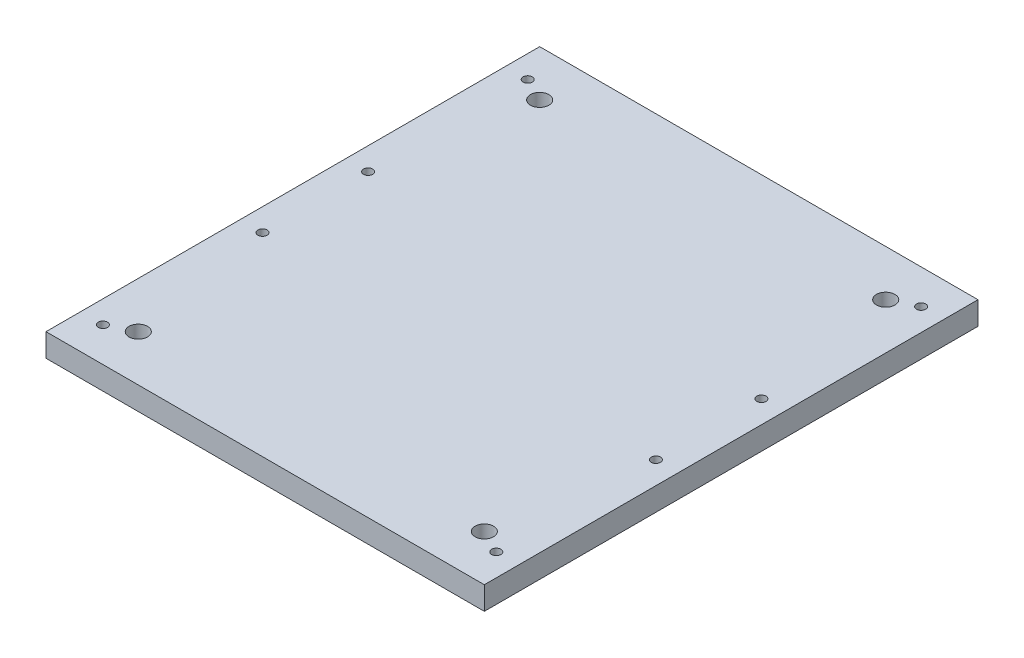
SolidWorks part; units mm, degrees
ref_plane "Front Plane" through (0, 0, 0) normal (0, 0, 1) x (1, 0, 0)
ref_plane "Top Plane" through (0, 0, 0) normal (0, 1, 0) x (1, 0, 0)
ref_plane "Right Plane" through (0, 0, 0) normal (1, 0, 0) x (0, 0, -1)
sketch "Sketch2" plane through (0, 0, 0) normal (0, 1, 0) x (1, 0, 0)
  line L0 (37.5, -43.5) -> (47.5, -43.5)
  line L1 (-47.5, -53.5) -> (47.5, -53.5)
  line L2 (-47.5, -53.5) -> (-47.5, 53.5)
  line L3 (-47.5, 53.5) -> (47.5, 53.5)
  line L4 (47.5, -53.5) -> (47.5, 53.5)
  line L5 (-47.5, -53.5) -> (47.5, 53.5) construction
  line L6 (-47.5, 53.5) -> (47.5, -53.5) construction
  line L7 (37.5, -43.5) -> (37.5, -53.5)
  line L8 (-55, 0) -> (55, 0) construction
  line L9 (0, -55) -> (0, 55) construction
  line L15 (-60, 66) -> (60, 66)
  line L16 (-60, 66) -> (-60, -66)
  line L17 (-60, -66) -> (60, -66)
  line L18 (60, 66) -> (60, -66)
  line L19 (-60, 66) -> (60, -66) construction
  line L20 (-60, -66) -> (60, 66) construction
  circle A1 centre (37.5, -43.5) radius 2
  circle A2 centre (37.5, 43.5) radius 2
  circle A3 centre (-37.5, -43.5) radius 2
  circle A4 centre (-37.5, 43.5) radius 2
  point P0 (0, 0)
  point P20 (0, 0)
  point P21 (0, 0)
  dimension "D3" = 10
  dimension "D5" = 4
  dimension "D1" = 95
  dimension "D2" = 107
  dimension "D4" = 10
  dimension "D6" = 120
  dimension "D7" = 132
extrude "Boss-Extrude1" add sketch "Sketch2" along normal blind 5 contours A1 L0 L4 L3 L2 L1 L7 A4 A2 A3 | A1 L7 L1 L4 L0
sketch "Sketch3" plane through (0, 5, 0) normal (0, 1, 0) x (1, 0, 0)
  line L5 (-47.515, 40.2371) -> (-32.4121, 40.2371) construction
  line L6 (-47.5, -53.5) -> (-47.5, 53.5) construction
  line L10 (-47.5, 17.2402) -> (-47.5, 40.2371)
  line L11 (-47.6, 40.3371) -> (-32.2822, 40.3371)
  line L12 (-32.2822, 40.3371) -> (-30.49, 37.2328)
  line L13 (-30.49, 17.1402) -> (-30.49, 37.2328)
  line L14 (-47.6, 17.1402) -> (-30.49, 17.1402)
  line L15 (-47.6, 17.1402) -> (-47.6, 40.3371)
  line L16 (-47.5, 40.2371) -> (-32.34, 40.2371) construction
  line L17 (-47.5, 17.2402) -> (-30.59, 17.2402) construction
  line L18 (-30.59, 17.2402) -> (-30.59, 37.206) construction
  line L19 (-32.34, 40.2371) -> (-30.59, 37.206) construction
  line L20 (0, 62.7045) -> (0, 59.4045) construction
  line L21 (32.2822, 40.3371) -> (30.49, 37.2328)
  line L22 (30.49, 17.1402) -> (30.49, 37.2328)
  line L23 (47.6, 17.1402) -> (30.49, 17.1402)
  line L24 (47.5, 17.2402) -> (47.5, 40.2371)
  line L25 (47.6, 40.3371) -> (32.2822, 40.3371)
  line L26 (-130.0965, 0) -> (-126.7965, 0) construction
  line L27 (47.5, -17.2402) -> (47.5, -40.2371)
  line L28 (47.6, -17.1402) -> (30.49, -17.1402)
  line L29 (30.49, -17.1402) -> (30.49, -37.2328)
  line L30 (32.2822, -40.3371) -> (30.49, -37.2328)
  line L31 (47.6, -40.3371) -> (32.2822, -40.3371)
  line L32 (-30.49, -17.1402) -> (-30.49, -37.2328)
  line L33 (-32.2822, -40.3371) -> (-30.49, -37.2328)
  line L34 (-47.6, -40.3371) -> (-32.2822, -40.3371)
  line L35 (-47.5, -17.2402) -> (-47.5, -40.2371)
  line L36 (-47.6, -17.1402) -> (-30.49, -17.1402)
  dimension "D1" = 0.1
sketch "Sketch4" plane through (0, 5, 0) normal (0, 1, 0) x (1, 0, 0)
  line L0 (-47.5, 53.5) -> (47.5, 53.5) construction
  circle A0 centre (42.63, 46.04) radius 1
  circle A1 centre (37.5, 43.5) radius 2 construction
  dimension "D1" = 2
  dimension "D2" = 7.46
  dimension "D3" = 5.13
sketch "Sketch6" plane through (0, 5, 0) normal (0, 1, 0) x (1, 0, 0)
  line L0 (32.2822, 40.3371) -> (32.2822, 17.1402)
  line L1 (47.6, 17.1402) -> (30.49, 17.1402) construction
  line L2 (18.8792, 40.3371) -> (18.8792, 17.1402)
  line L3 (18.8792, 28.7386) -> (32.2822, 28.7386)
ref_plane "Plane1" through (0, 0, -28.7386) normal (0, 0, -1) x (-1, 0, 0)
extrude "Cut-Extrude1" cut sketch "Sketch4" against normal up to next
mirror "Mirror1" about plane through (0, 0, -28.7386) normal (0, 0, -1) of "Cut-Extrude1"
mirror "Mirror2" about plane through (0, 0, 0) normal (1, 0, 0) of "Mirror1", "Cut-Extrude1" second plane through (0, 0, 0) second plane normal (0, 0, 1)
